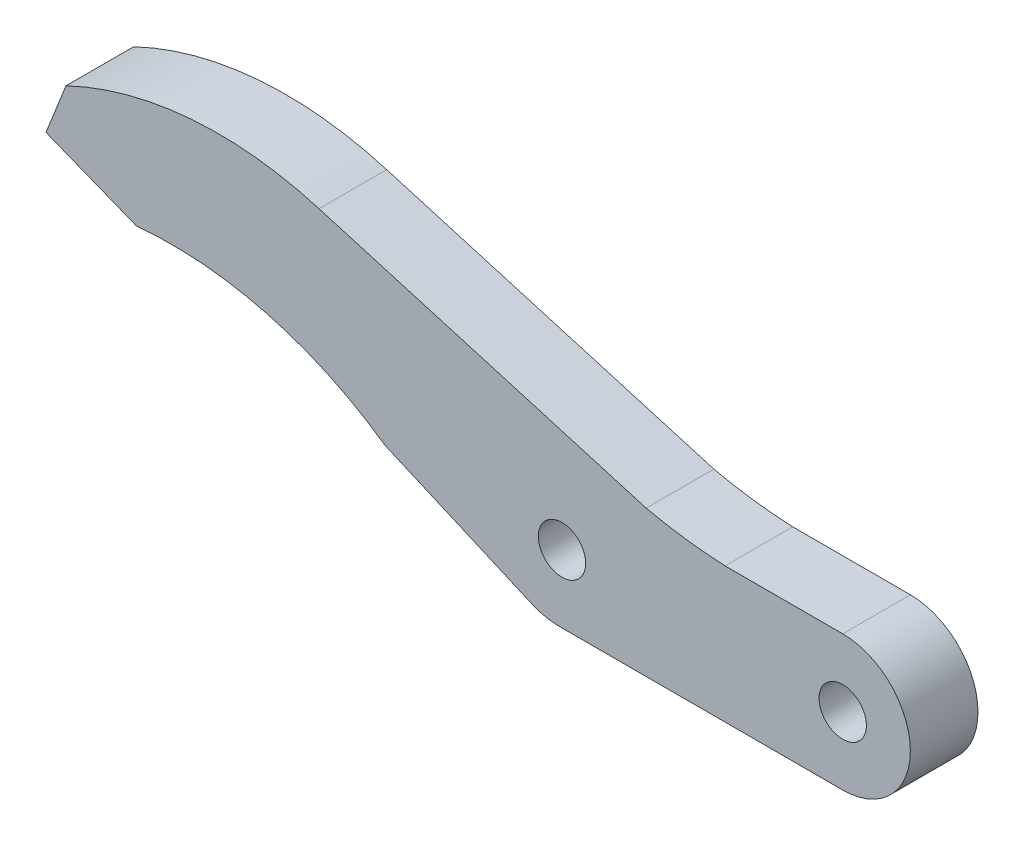
SolidWorks part; units mm, degrees
ref_plane "Front Plane" through (0, 0, 0) normal (0, 0, 1) x (1, 0, 0)
ref_plane "Top Plane" through (0, 0, 0) normal (0, 1, 0) x (1, 0, 0)
ref_plane "Right Plane" through (0, 0, 0) normal (1, 0, 0) x (0, 0, -1)
sketch "Sketch2" plane through (0, 0, 0) normal (0, 0, 1) x (1, 0, 0)
  line L0 (-33.8284, 0.1478) -> (-22, -5)
  line L1 (0, -5) -> (-22, -5)
  line L2 (-52.1984, 5) -> (-58.8916, 7.6535)
  line L3 (-58.8916, 7.6535) -> (-57.4174, 11.3719)
  line L4 (0, 5) -> (-8.7, 5)
  line L6 (-38.7093, 12.8595) -> (-14.5233, 5.7827)
  line L7 (-58.8916, 7.6535) -> (-20.9169, 7.6535) construction
  line L8 (0, 0) -> (-20.75, 0) construction
  circle A0 centre (0, 0) radius 1.75
  arc A1 (0, -5) -> (0, 5) centre (0, 0) ccw
  circle A2 centre (-20.75, 0) radius 1.75
  arc A3 (-33.8284, 0.1478) -> (-52.1984, 5) centre (-49.5655, -22.2319) ccw
  arc A4 (-8.7, 5) -> (-14.5233, 5.7827) centre (-7.1526, 38.5643) cw
  arc A5 (-38.7093, 12.8595) -> (-57.4174, 11.3719) centre (-46.1413, -12.0556) ccw
  dimension "D1" = 5
  dimension "D2" = 3.5
  dimension "D4" = 25.2
  dimension "D6" = 33.6
  dimension "D7" = 26
  dimension "D8" = 27.3589
  dimension "D19" = 3.5
  dimension "D3" = 22
  dimension "D5" = 8.7
  dimension "D9" = 12.9
  dimension "D10" = 7.2
  dimension "D11" = 4
  dimension "D12" = 156.481
  dimension "D13" = 68.374
  dimension "D14" = 163.691
  dimension "D15" = 19
  dimension "D16" = 18.7672
  dimension "D17" = 5.8757
  dimension "D18" = 20.75
extrude "Boss-Extrude1" add sketch "Sketch2" along normal blind 5
fillet "Fillet1" radius 5 1 edges at (-22, -5, 2.5)
ref_point "Point1"
ref_point "Point2"
